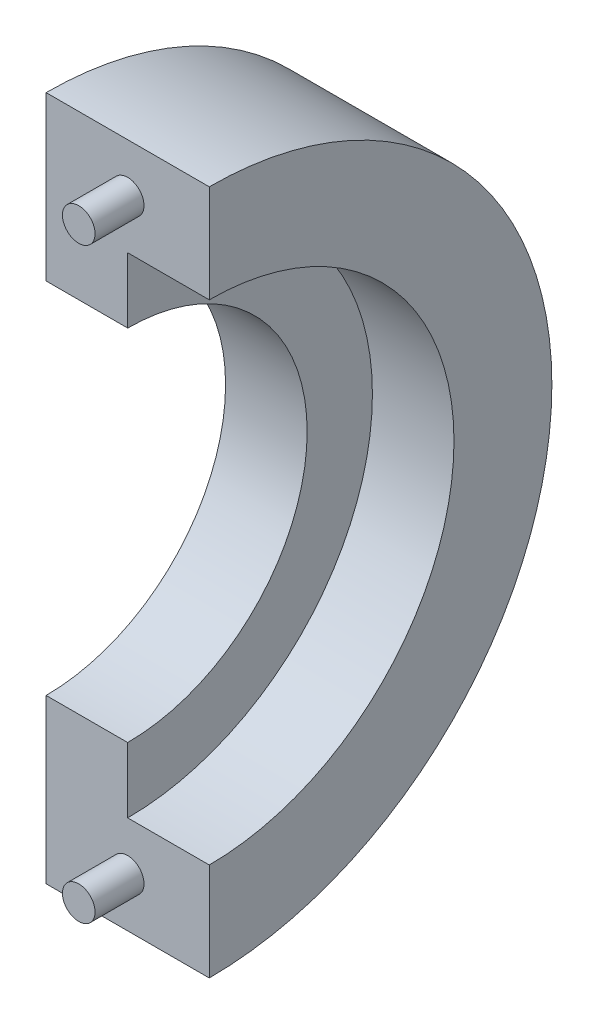
SolidWorks part; units mm, degrees
ref_plane "Front Plane" through (0, 0, 0) normal (0, 0, 1) x (1, 0, 0)
ref_plane "Top Plane" through (0, 0, 0) normal (0, 1, 0) x (1, 0, 0)
ref_plane "Right Plane" through (0, 0, 0) normal (1, 0, 0) x (0, 0, -1)
sketch "Sketch1" plane through (0, 0, 0) normal (0, 0, 1) x (1, 0, 0)
  line L0 (0, 0) -> (-15.4049, 0) construction
  line L1 (-2.5, 5.5) -> (-5, 5.5)
  line L2 (0, 7.5) -> (0, 10.5)
  line L3 (0, 10.5) -> (-5, 10.5)
  line L4 (-5, 5.5) -> (-5, 10.5)
  line L7 (0, 7.5) -> (-2.5, 7.5)
  line L8 (-2.5, 5.5) -> (-2.5, 7.5)
  dimension "D1" = 5
  dimension "D3" = 2.5
  dimension "D4" = 2
  dimension "D5" = 5.5
revolve "Revolve1" add sketch "Sketch1" angle 180 about L0
sketch "Sketch2" plane through (0, 0, 0) normal (0, 0, 1) x (1, 0, 0)
  line L0 (-5, 10.5) -> (-5, 5.5) construction
  line L1 (0, 10.5) -> (-5, 10.5) construction
  circle A0 centre (-2.5, 9) radius 0.5
  dimension "D1" = 1
  dimension "D2" = 2.5
  dimension "D3" = 1.5
extrude "Boss-Extrude1" add sketch "Sketch2" along normal blind 1.5
mirror "Mirror1" about plane through (0, 0, 0) normal (0, 1, 0) of "Boss-Extrude1"
